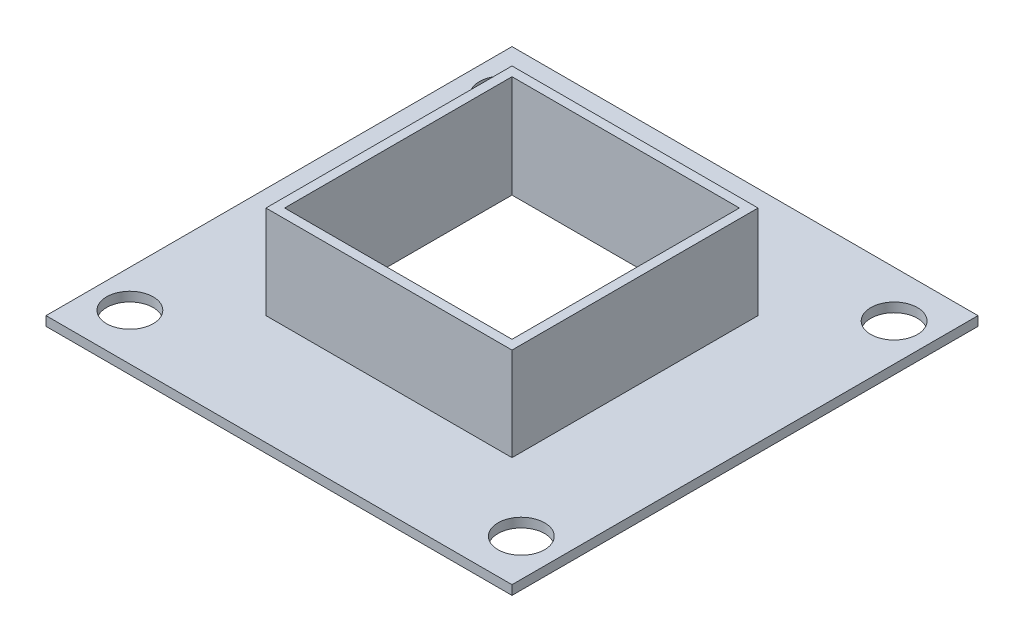
SolidWorks part; units mm, degrees
material "Plain Carbon Steel"
ref_plane "Front Plane" through (0, 0, 0) normal (0, 0, 1) x (1, 0, 0)
ref_plane "Top Plane" through (0, 0, 0) normal (0, 1, 0) x (1, 0, 0)
ref_plane "Right Plane" through (0, 0, 0) normal (1, 0, 0) x (0, 0, -1)
sketch "Sketch1" plane through (0, 0, 0) normal (0, 1, 0) x (1, 0, 0)
  line L0 (-33.528, 33.528) -> (-33.528, -33.528)
  line L1 (-30.988, 30.988) -> (30.988, 30.988)
  line L2 (-30.988, 30.988) -> (-30.988, -30.988)
  line L3 (-30.988, -30.988) -> (30.988, -30.988)
  line L4 (30.988, 30.988) -> (30.988, -30.988)
  line L5 (-30.988, 30.988) -> (30.988, -30.988) construction
  line L6 (-30.988, -30.988) -> (30.988, 30.988) construction
  line L7 (-33.528, -33.528) -> (33.528, -33.528)
  line L8 (33.528, 33.528) -> (33.528, -33.528)
  line L9 (-33.528, 33.528) -> (33.528, 33.528)
  point P0 (0, 0)
  dimension "D1" = 61.976
  dimension "D2" = 2.54
extrude "Boss-Extrude1" add sketch "Sketch1" along normal blind 25.4
sketch "Sketch3" plane through (0, 0, 0) normal (0, -1, 0) x (1, 0, 0)
  line L1 (-63.5, -63.5) -> (63.5, -63.5)
  line L2 (-63.5, -63.5) -> (-63.5, 63.5)
  line L3 (-63.5, 63.5) -> (63.5, 63.5)
  line L4 (63.5, -63.5) -> (63.5, 63.5)
  line L5 (-63.5, -63.5) -> (63.5, 63.5) construction
  line L6 (-63.5, 63.5) -> (63.5, -63.5) construction
  point P0 (0, 0)
  dimension "D1" = 127
extrude "Boss-Extrude2" add sketch "Sketch3" along normal blind 2.54
sketch "Sketch4" plane through (0, 0, 0) normal (0, 1, 0) x (1, 0, 0)
  line L0 (-63.5, -63.5) -> (-63.5, 63.5) construction
  line L1 (-63.5, 63.5) -> (63.5, 63.5) construction
  line L2 (63.5, 63.5) -> (63.5, -63.5) construction
  line L3 (63.5, -63.5) -> (-63.5, -63.5) construction
  circle A0 centre (-53.34, 50.8) radius 6.35
  circle A1 centre (53.34, 50.8) radius 6.35
  circle A2 centre (53.34, -50.8) radius 6.35
  circle A3 centre (-53.34, -50.8) radius 6.35
  dimension "D1" = 10.16
  dimension "D2" = 12.7
  dimension "D3" = 10.16
  dimension "D4" = 12.7
  dimension "D5" = 12.7
extrude "Cut-Extrude1" cut sketch "Sketch4" against normal through all
sketch "Sketch6" plane through (0, 0, 0) normal (0, 1, 0) x (1, 0, 0)
  line L4 (-30.988, 30.988) -> (-30.988, -30.988)
  line L5 (-30.988, -30.988) -> (30.988, -30.988)
  line L6 (30.988, -30.988) -> (30.988, 30.988)
  line L7 (30.988, 30.988) -> (-30.988, 30.988)
  line L8 (-30.988, 30.988) -> (-30.988, -30.988)
  line L9 (-30.988, -30.988) -> (30.988, -30.988)
  line L10 (30.988, -30.988) -> (30.988, 30.988)
  line L11 (30.988, 30.988) -> (-30.988, 30.988)
  dimension "D1" = 0
extrude "Cut-Extrude2" cut sketch "Sketch6" against normal through all
